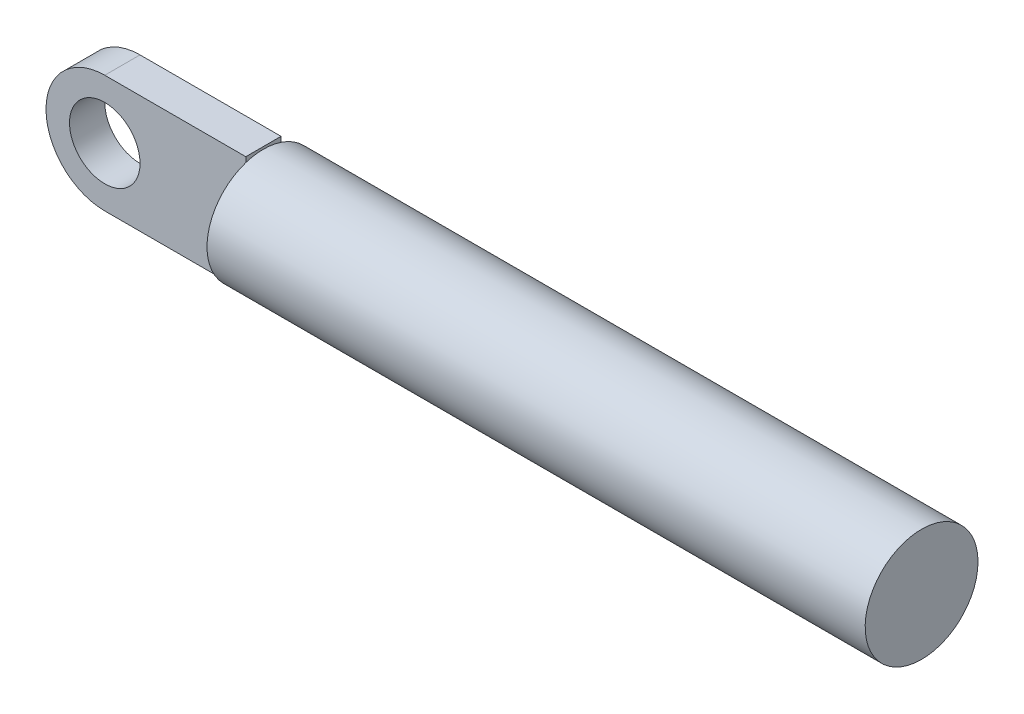
SolidWorks part; units mm, degrees
ref_plane "前视基准面" through (0, 0, 0) normal (0, 0, 1) x (1, 0, 0)
ref_plane "上视基准面" through (0, 0, 0) normal (0, 1, 0) x (1, 0, 0)
ref_plane "右视基准面" through (0, 0, 0) normal (1, 0, 0) x (0, 0, -1)
sketch "草图1" plane through (0, 0, 0) normal (0, 0, 1) x (1, 0, 0)
  line L0 (0, 59.5317) -> (0, -68.87) construction
  line L1 (-64.7845, 0) -> (86.5739, 0) construction
  line L2 (0, 25) -> (60, 25)
  line L3 (60, 25) -> (60, -25)
  line L4 (60, -25) -> (0, -25)
  arc A0 (0, 25) -> (0, -25) centre (0, 0) ccw
  circle A1 centre (0, 0) radius 15
  dimension "D1" = 50
  dimension "D2" = 30
  dimension "D3" = 60
extrude "凸台-拉伸1" add sketch "草图1" along normal blind 15
sketch "草图2" plane through (60, 0, 0) normal (1, 0, 0) x (0, 0, -1)
  line L0 (-30.8877, 0) -> (22.2142, 0) construction
  line L1 (-7.5, 25) -> (-7.5, -27.4596) construction
  line L2 (-15, 25) -> (0, 25) construction
  circle A0 centre (-7.5, 0) radius 24
  dimension "D1" = 48
extrude "凸台-拉伸2" add sketch "草图2" along normal blind 280 contours A0
scale "缩放比例1" bodies to scale 107 scale about origin uniform scaling yes scale factor 0.6
